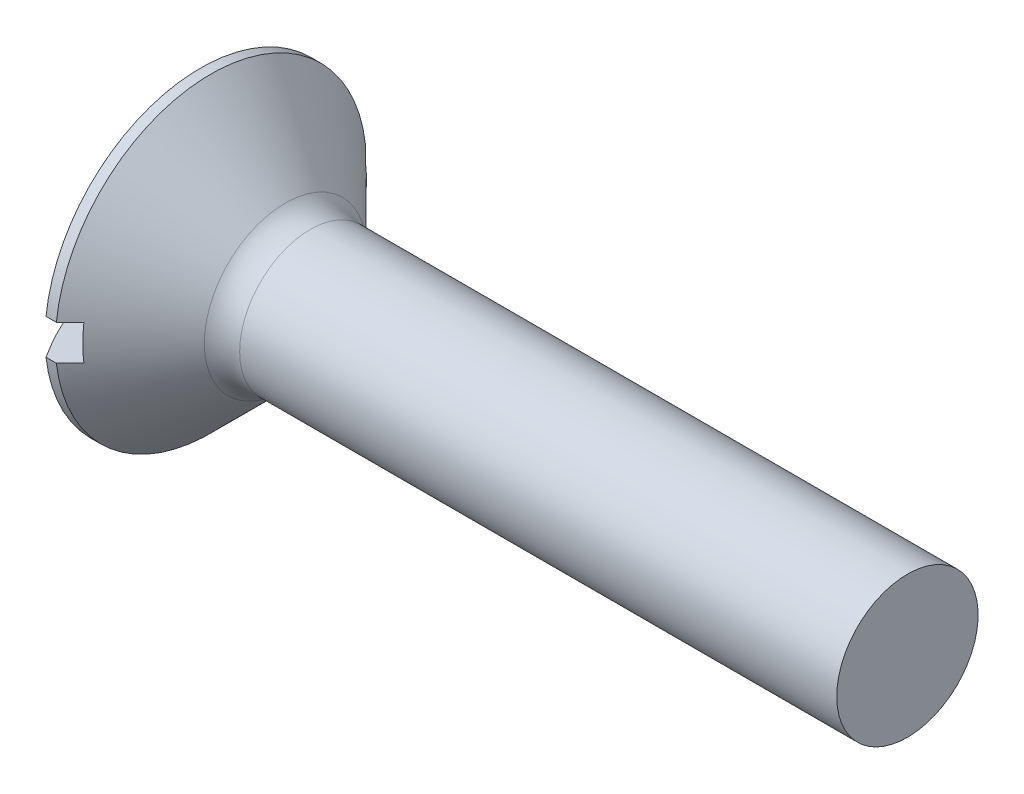
SolidWorks part; units mm, degrees
ref_plane "Front" through (0, 0, 0) normal (0, 0, 1) x (1, 0, 0)
ref_plane "Top" through (0, 0, 0) normal (0, 1, 0) x (1, 0, 0)
ref_plane "Right" through (0, 0, 0) normal (1, 0, 0) x (0, 0, -1)
sketch "Ske-Screw" plane through (0, 0, 0) normal (0, 0, 1) x (1, 0, 0)
  line L0 (0.6593, 2.2) -> (0.8058, 2.2)
  line L1 (0.6593, 0) -> (0, 0)
  line L2 (2.2129, 1) -> (10.6593, 1)
  line L3 (10.6593, 1) -> (10.6593, 0)
  line L4 (10.6593, 0) -> (0.6593, 0)
  line L5 (-1.3499, 0) -> (8.9842, 0) construction
  line L6 (0.8058, 2.2) -> (1.8593, 1.1464)
  arc A0 (0.6593, 2.2) -> (0, 0) centre (4, 0) ccw
  arc A1 (1.8593, 1.1464) -> (2.2129, 1) centre (2.2129, 1.5) ccw
  dimension "rf" = 4
  dimension "r" = 0.5
  dimension "l" = 10
  dimension "dk" = 4.4
  dimension "d" = 2
  dimension "k" = 1.2
  dimension "D3" = 45
revolve "Base" add sketch "Ske-Screw" angle 360 about L5
cosmetic thread "ThreadCosmetic1" [suppressed] parameters "D1"=8.8, "D2"=1.567
sketch "Ske-Slot" plane through (0, 0, 0) normal (0, 0, 1) x (1, 0, 0)
  line L1 (-1.3728, 0) -> (2.5237, 0) construction
  line L2 (0, -0.25) -> (1, -0.25)
  line L3 (0, -0.25) -> (0, 0.25)
  line L4 (0, 0.25) -> (1, 0.25)
  line L5 (1, -0.25) -> (1, 0.25)
  arc A0 (0.6593, 2.2) -> (0.6593, -2.2) centre (4, 0) ccw construction
  dimension "n" = 0.5
  dimension "t" = 1
extrude "Slot" cut sketch "Ske-Slot" against normal through all and the other way through all
sketch "Sketch1" plane through (0, 0, 0) normal (0, 0, 1) x (1, 0, 0)
  line L0 (5.8578, 0) -> (-1.624, 0) construction
  line L1 (1.8593, 5.7835) -> (-14.3407, 5.7835)
  line L2 (1.8593, 5.7835) -> (1.8593, 0.7835)
  line L3 (1.8593, 0.7835) -> (-15.3407, 0.7835)
  line L4 (-14.3407, 5.7835) -> (-14.3407, 1)
  line L6 (0.6593, 2.2) -> (0.6593, 0.25) construction
  line L7 (10.6593, -1) -> (10.6593, 1) construction
  line L9 (2.2129, 1) -> (10.6593, 1) construction
  line L10 (-14.3407, 1) -> (-15.3407, 0.7835)
  dimension "b" = 25
  dimension "D4" = 5
  dimension "x" = 1
  dimension "k" = 1.2
  dimension "D2" = 1.567
sketch "Sketch2" plane through (0, 0, 0) normal (0, 0, 1) x (1, 0, 0)
  line L0 (10.6593, 0.8125) -> (10.7676, 1)
  line L1 (10.7676, 1) -> (10.7676, 1.2165)
  line L2 (10.7676, 1.2165) -> (10.5511, 1.2165)
  line L3 (10.5511, 1.2165) -> (10.5511, 1)
  line L4 (10.5511, 1) -> (10.6593, 0.8125)
  line L5 (0, 0) -> (7.193, 0) construction
  line L6 (10.6593, -1) -> (10.6593, 1) construction
  dimension "D1" = 2
  dimension "D2" = 0.2165
revolve "Cut-Revolve10" [suppressed] cut sketch "Sketch2" angle 360 about L5
pattern_linear "LPattern10" [suppressed] count 33 spacing 0.2598 along (1, 0, 0)
equation "\"D1@Sketch2\" = \"d@Ske-Screw\""
equation "\"D2@Sketch2\" =  ( \"d@Ske-Screw\" - \"D2@ThreadCosmetic1\" )  / 2"
equation "\"D3@LPattern10\" = \"D2@Sketch2\" * 1.2"
equation "\"D1@LPattern10\" = \"D1@ThreadCosmetic1\" / \"D3@LPattern10\" - 1"
